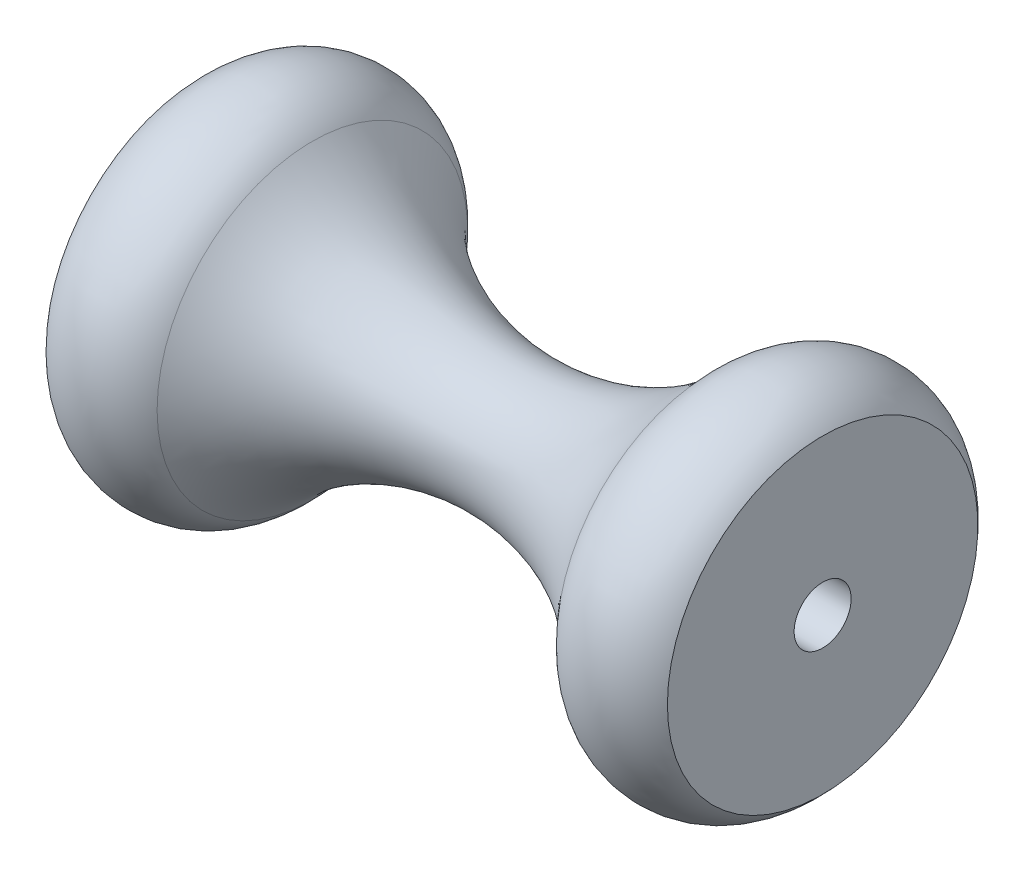
SolidWorks part; units mm, degrees
ref_plane "Front Plane" through (0, 0, 0) normal (0, 0, 1) x (1, 0, 0)
ref_plane "Top Plane" through (0, 0, 0) normal (0, 1, 0) x (1, 0, 0)
ref_plane "Right Plane" through (0, 0, 0) normal (1, 0, 0) x (0, 0, -1)
sketch "Sketch1" plane through (0, 0, 0) normal (0, 0, 1) x (1, 0, 0)
  line L0 (-25, 0) -> (25, 0)
  line L1 (-25, 0) -> (-25, -12.5)
  line L2 (25, 0) -> (25, -12.5)
  line L3 (25, -12.5) -> (-25, -12.5) construction
  line L4 (0, 0) -> (0, -26) construction
  arc A0 (16.0857, -12.5) -> (-16.0857, -12.5) centre (0, -26) ccw
  arc A1 (-25, -12.5) -> (-16.0857, -12.5) centre (-20.5429, -8.7593) ccw
  arc A2 (16.0857, -12.5) -> (25, -12.5) centre (20.5429, -8.7593) ccw
  dimension "D3" = 42
  dimension "D1" = 50
  dimension "D2" = 12.5
  dimension "D4" = 26
revolve "Revolve1" add sketch "Sketch1" angle 360 about L0
sketch "Sketch2" plane through (25, 0, 0) normal (1, 0, 0) x (0, 0, -1)
  circle A0 centre (0, 0) radius 2.2941
extrude "Cut-Extrude1" cut sketch "Sketch2" against normal through all
